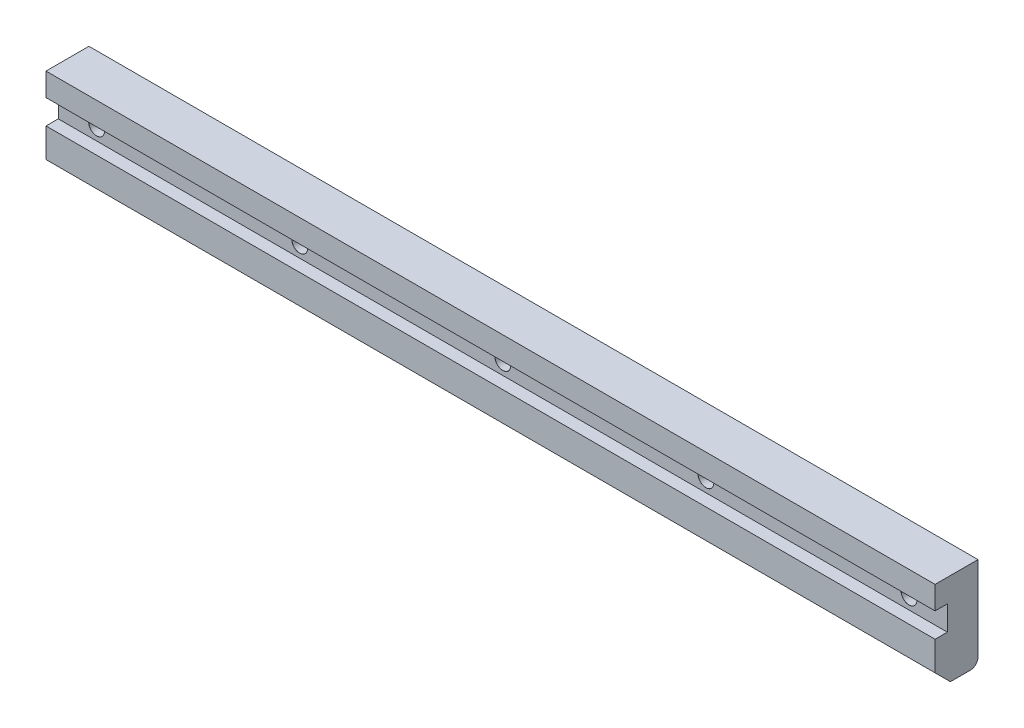
SolidWorks part; units mm, degrees
ref_plane "Front Plane" through (0, 0, 0) normal (0, 0, 1) x (1, 0, 0)
ref_plane "Top Plane" through (0, 0, 0) normal (0, 1, 0) x (1, 0, 0)
ref_plane "Right Plane" through (0, 0, 0) normal (1, 0, 0) x (0, 0, -1)
sketch "Sketch1" plane through (0, 0, 0) normal (1, 0, 0) x (0, 0, -1)
  line L0 (0, 0) -> (-28, 0)
  line L1 (-28, 0) -> (-28, -15)
  line L2 (-28, -15) -> (-20, -15)
  line L3 (-20, -15) -> (-20, -31)
  line L4 (-20, -31) -> (-28, -31)
  line L5 (-28, -31) -> (-28, -50)
  line L6 (-28, -50) -> (-18, -60)
  line L7 (-18, -60) -> (-5, -60)
  line L8 (0, -55) -> (0, 0)
  arc A0 (-5, -60) -> (0, -55) centre (-5, -55) ccw
  point P13 (0, -60)
  dimension "D8" = 5
  dimension "D1" = 28
  dimension "D2" = 8
  dimension "D3" = 15
  dimension "D4" = 16
  dimension "D5" = 10
  dimension "D6" = 60
  dimension "D7" = 45
extrude "Boss-Extrude1" add sketch "Sketch1" along normal mid plane 580
sketch "Sketch2" plane through (0, 0, 20) normal (0, 0, 1) x (1, 0, 0)
  line L0 (-290, -15) -> (-290, -31) construction
  line L1 (290, 0) -> (-290, 0) construction
  point P0 (-265, -23)
  point P7 (-132.5, -23)
  point P8 (0, -23)
  point P9 (132.5, -23)
  point P10 (265, -23)
  dimension "D1" = 25
  dimension "D2" = 23
  dimension "D3" = 5
hole_wizard "Tap Drill for M10 Helicoil1" positions "3DSketch1" profile "Sketch3" hole size "M10x1.25" standard "ANSI Metric" end condition through all
sketch3d "3DSketch1"
  point P0 (-265, -23, 20)
  point P3 (-132.5, -23, 20)
  point P6 (0, -23, 20)
  point P9 (132.5, -23, 20)
  point P12 (265, -23, 20)
sketch "Sketch3" plane through (-265, -23, 20) normal (1, 0, 0) x (0, -1, 0)
  line L0 (0, 0) -> (0, 20)
  line L1 (0, 20) -> (5.125, 20)
  line L2 (5.125, 20) -> (5.125, 0.025)
  line L3 (5.125, 0.025) -> (5.15, 0)
  line L5 (5.15, 0) -> (0, 0)
  line L6 (-5.125, 0.025) -> (-5.15, 0) construction
  line L11 (0, -6.35) -> (0, 107.95) construction
  dimension "Thru Hole Dia." = 10.25
  dimension "Thru Hole Depth" = 20
  dimension "Near C'Sink Dia." = 10.3
  dimension "Near C'Sink Angle" = 90
